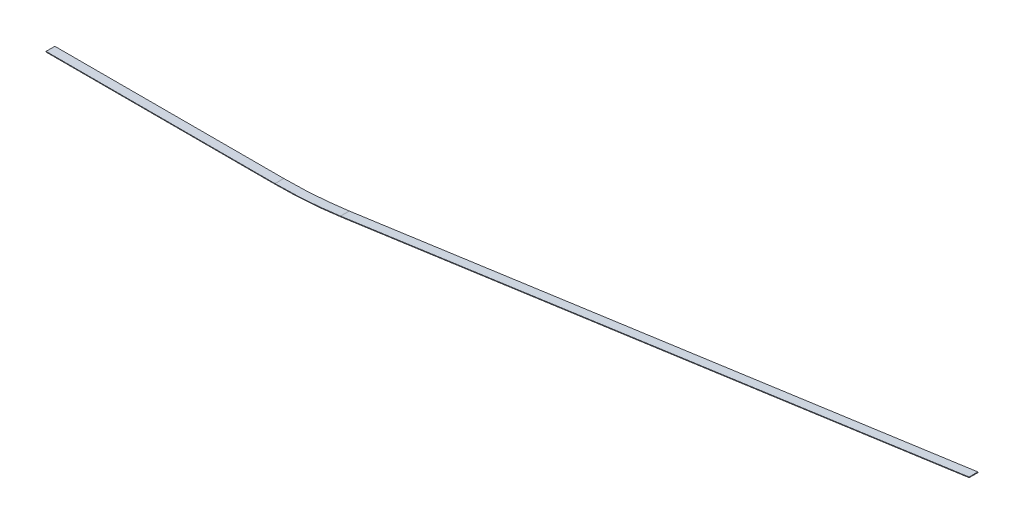
SolidWorks part; units mm, degrees
ref_plane "Front Plane" through (0, 0, 0) normal (0, 0, 1) x (1, 0, 0)
ref_plane "Top Plane" through (0, 0, 0) normal (0, 1, 0) x (1, 0, 0)
ref_plane "Right Plane" through (0, 0, 0) normal (1, 0, 0) x (0, 0, -1)
sketch "Sketch1" plane through (0, 0, 0) normal (0, 0, 1) x (1, 0, 0)
  line L0 (5501.6922, 2965.8674) -> (5501.6922, 2966.5024)
  line L1 (5501.6922, 2966.5024) -> (5748.7444, 2966.5024)
  line L2 (5501.6922, 2965.8674) -> (5748.7444, 2965.8674)
  line L3 (5819.4443, 2971.4462) -> (6497.6422, 3066.7607)
  line L4 (5819.5327, 2970.8174) -> (6497.7306, 3066.1319)
  line L5 (6497.7306, 3066.1319) -> (6497.6422, 3066.7607)
  arc A0 (5748.7444, 2966.5024) -> (5819.4443, 2971.4462) centre (5748.7444, 3474.5024) ccw
  arc A1 (5748.7444, 2965.8674) -> (5819.5327, 2970.8174) centre (5748.7444, 3474.5024) ccw
extrude "Boss-Extrude1" add sketch "Sketch1" along normal blind 9.525
